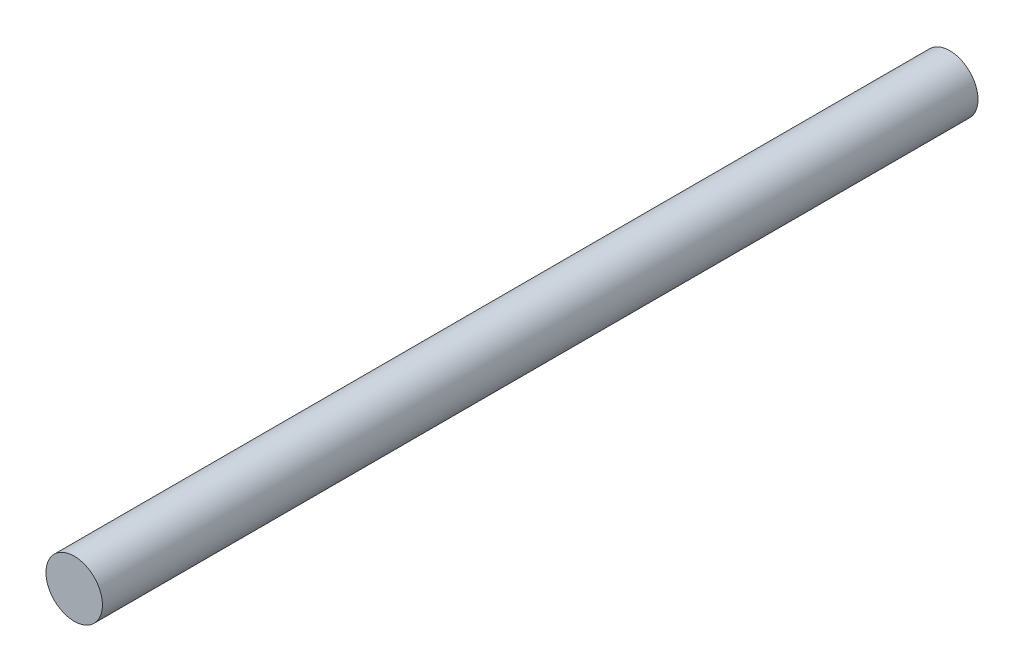
SolidWorks part; units mm, degrees
ref_plane "Front Plane" through (0, 0, 0) normal (0, 0, 1) x (1, 0, 0)
ref_plane "Top Plane" through (0, 0, 0) normal (0, 1, 0) x (1, 0, 0)
ref_plane "Right Plane" through (0, 0, 0) normal (1, 0, 0) x (0, 0, -1)
sketch "Sketch1" plane through (0, 0, 0) normal (0, 0, 1) x (1, 0, 0)
  circle A0 centre (0, 0) radius 2
extrude "Boss-Extrude1" add sketch "Sketch1" along normal blind 62
